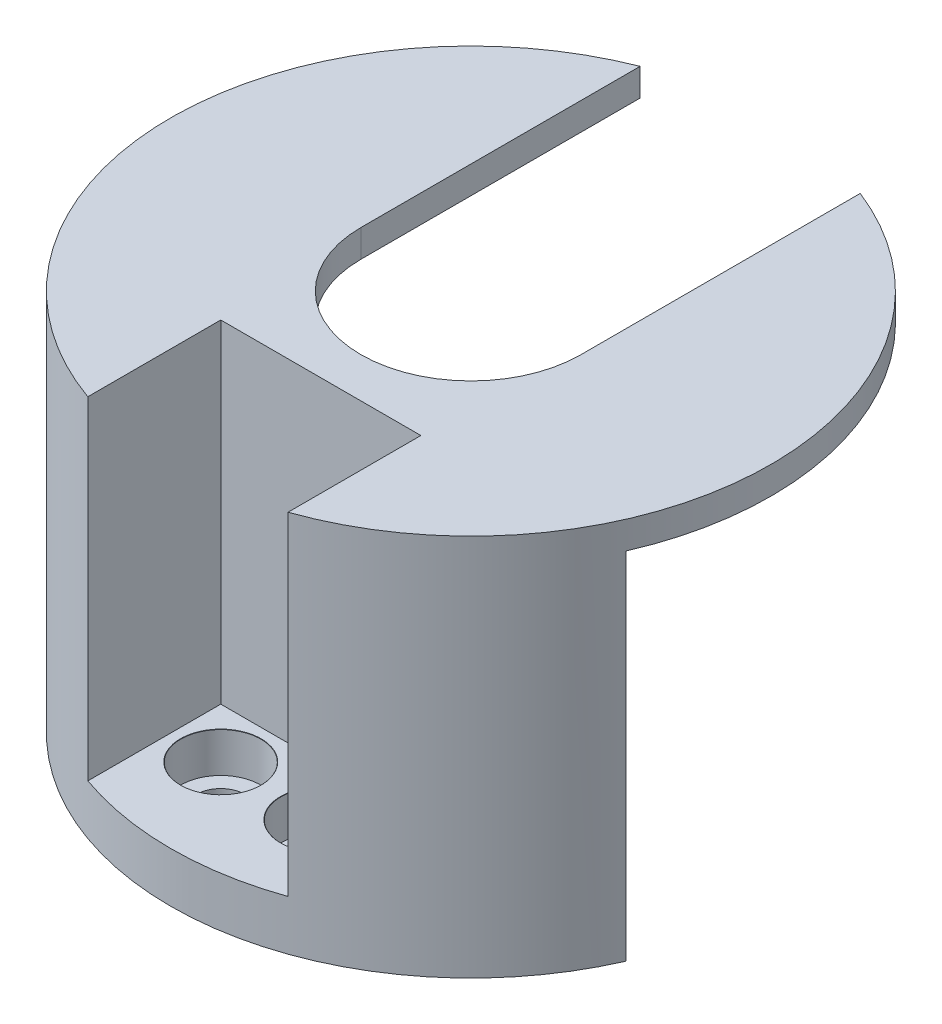
SolidWorks part; units mm, degrees
ref_plane "Front Plane" through (0, 0, 0) normal (0, 0, 1) x (1, 0, 0)
ref_plane "Top Plane" through (0, 0, 0) normal (0, 1, 0) x (1, 0, 0)
ref_plane "Right Plane" through (0, 0, 0) normal (1, 0, 0) x (0, 0, -1)
sketch "Sketch1" plane through (0, 0, 0) normal (0, 1, 0) x (1, 0, 0)
  circle A0 centre (0, 0) radius 30
  dimension "D1" = 60
extrude "Boss-Extrude1" add sketch "Sketch1" along normal mid plane 38.25
sketch "Sketch5" plane through (0, 0, 0) normal (1, 0, 0) x (0, 0, -1)
  line L0 (-30, 19.125) -> (-30, -19.125) construction
  line L1 (30, 16.375) -> (-12, 16.375)
  line L2 (30, 16.375) -> (30, -19.125)
  line L3 (30, -19.125) -> (-12, -19.125)
  line L4 (-12, 16.375) -> (-12, -19.125)
  line L5 (30, 16.375) -> (-12, -19.125) construction
  line L6 (30, -19.125) -> (-12, 16.375) construction
  line L7 (30, 19.125) -> (-30, 19.125) construction
  line L8 (-30, -19.125) -> (30, -19.125) construction
  line L9 (30, -19.125) -> (30, 19.125) construction
  point P0 (9, -1.375)
  dimension "D1" = 18
  dimension "D2" = 2.75
extrude "Cut-Extrude1" cut sketch "Sketch5" against normal mid plane 105
sketch "Sketch7" plane through (0, 19.125, 0) normal (0, 1, 0) x (1, 0, 0)
  line L1 (-11, 50) -> (11, 50)
  line L2 (-11, 50) -> (-11, 0)
  line L3 (-11, 0) -> (11, 0)
  line L4 (11, 50) -> (11, 0)
  line L5 (-11, 50) -> (11, 0) construction
  line L6 (-11, 0) -> (11, 50) construction
  circle A0 centre (0, 0) radius 11
  point P3 (0, 25)
  circle M1 centre (0, 0) radius 30
  dimension "D1" = 22
  dimension "D2" = 50
extrude "Cut-Extrude3" cut sketch "Sketch7" against normal mid plane 105 contours A0 L4 L2 M1 | L3 A0 | L3 A0
sketch "Sketch8" plane through (0, 19.125, 0) normal (0, 1, 0) x (1, 0, 0)
  line L5 (10, -15) -> (-10, -15)
  line L6 (10, -15) -> (10, -30)
  line L7 (10, -30) -> (-10, -30)
  line L8 (-10, -15) -> (-10, -30)
  line L9 (10, -15) -> (-10, -30) construction
  line L10 (10, -30) -> (-10, -15) construction
  circle A0 centre (0, 0) radius 30
  arc A1 (-11, 27.9106) -> (11, 27.9106) centre (0, 0) ccw construction
  point P6 (0, -22.5)
  point P11 (0, 0)
  dimension "D1" = 15
  dimension "D2" = 20
extrude "Cut-Extrude4" cut sketch "Sketch8" against normal offset from surface (33.25 mm away) 5
sketch "Sketch9" plane through (0, -14.125, 0) normal (0, 1, 0) x (1, 0, 0)
  line L0 (0, 0) -> (0, -20) construction
  line L1 (-5, -20) -> (5, -20) construction
  circle A0 centre (-5, -20) radius 1.25
  circle A1 centre (5, -20) radius 1.25
  point P4 (0, 0)
  point P8 (0, 0)
  point P9 (0, 0)
  point P10 (0, 0)
  dimension "D1" = 2.5
  dimension "D2" = 2.5
  dimension "D3" = 20
  dimension "D4" = 5
  dimension "D5" = 5
hole_wizard "CBORE for M4 SHCS1" positions "Sketch10" profile "Sketch11" counterbore size "M4" standard "ANSI Metric"
sketch "Sketch10" plane through (0, -14.125, 0) normal (0, 1, 0) x (1, 0, 0)
  point P0 (-5, -20)
  point P3 (5, -20)
sketch "Sketch11" plane through (-5, -14.125, 20) normal (1, 0, 0) x (0, 0, 1)
  line L0 (0, 0) -> (0, 7.4421)
  line L1 (0, 7.4421) -> (2.4, 6)
  line L2 (2.4, 6) -> (2.4, 4)
  line L3 (2.4, 4) -> (4, 4)
  line L5 (4, 4) -> (4, 0.025)
  line L6 (4, 0.025) -> (4.025, 0)
  line L7 (4.025, 0) -> (0, 0)
  line L8 (-4, 0.025) -> (-4.025, 0) construction
  line L10 (0, 7.4421) -> (-2.4, 6) construction
  line L11 (0, -6.35) -> (0, 107.95) construction
  dimension "Hole Dia." = 4.8
  dimension "Hole Depth" = 6
  dimension "C'Bore Dia." = 8
  dimension "C'Bore Depth" = 4
  dimension "Near C'Sink Dia." = 8.05
  dimension "Near C'Sink Angle" = 90
  dimension "Drill Angle" = 118
